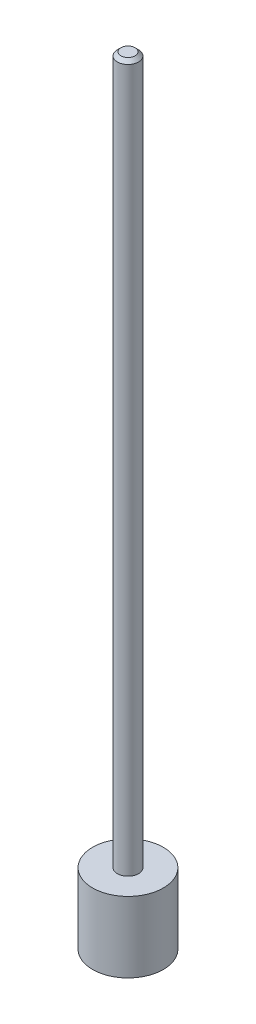
SolidWorks part; units mm, degrees
ref_plane "Front Plane" through (0, 0, 0) normal (0, 0, 1) x (1, 0, 0)
ref_plane "Top Plane" through (0, 0, 0) normal (0, 1, 0) x (1, 0, 0)
ref_plane "Right Plane" through (0, 0, 0) normal (1, 0, 0) x (0, 0, -1)
sketch "Sketch1" plane through (0, 0, 0) normal (0, 1, 0) x (1, 0, 0)
  circle A0 centre (0, 0) radius 5
  dimension "D1" = 10
extrude "Boss-Extrude1" add sketch "Sketch1" along normal blind 10
sketch "Sketch2" plane through (0, 10, 0) normal (0, 1, 0) x (1, 0, 0)
  circle A0 centre (0, 0) radius 1.5
  dimension "D1" = 3
extrude "Boss-Extrude2" add sketch "Sketch2" along normal blind 100
chamfer "Chamfer1" distance 0.5 angle 45 1 edges at (0, 110, 1.5)
